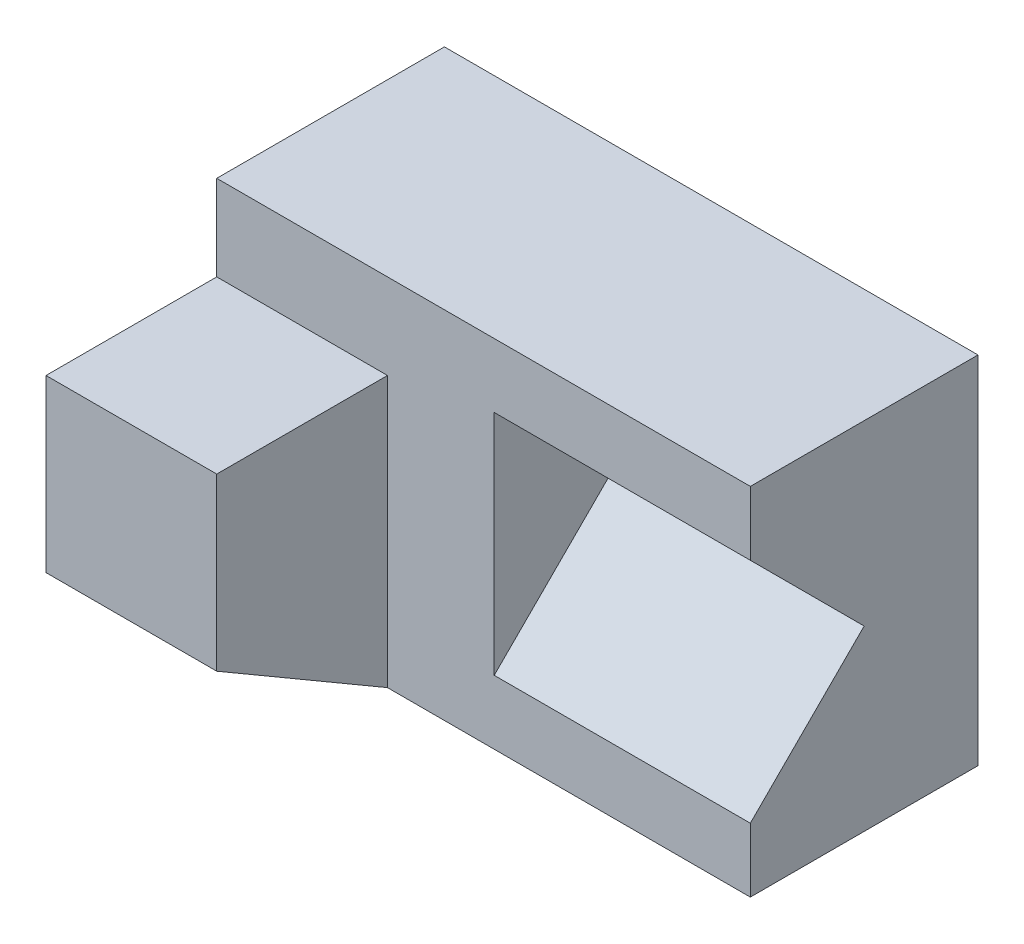
SolidWorks part; units mm, degrees
ref_plane "Front Plane" through (0, 0, 0) normal (0, 0, 1) x (1, 0, 0)
ref_plane "Top Plane" through (0, 0, 0) normal (0, 1, 0) x (1, 0, 0)
ref_plane "Right Plane" through (0, 0, 0) normal (1, 0, 0) x (0, 0, -1)
sketch "Sketch1" plane through (0, 0, 0) normal (0, 0, 1) x (1, 0, 0)
  line L1 (0, 0) -> (75, 0)
  line L2 (0, 0) -> (0, 50)
  line L3 (0, 50) -> (75, 50)
  line L4 (75, 0) -> (75, 50)
  dimension "D1" = 75
  dimension "D2" = 50
extrude "Boss-Extrude1" add sketch "Sketch1" along normal blind 32
sketch "Sketch2" plane through (75, 0, 0) normal (1, 0, 0) x (0, 0, -1)
  line L0 (-32, 41) -> (-16, 25)
  line L1 (-32, 0) -> (-32, 50) construction
  line L2 (-16, 25) -> (-32, 9)
  line L3 (-32, 50) -> (0, 50) construction
  line L4 (-32, 0) -> (0, 0) construction
  line L5 (0, 0) -> (0, 50) construction
  line L6 (-32, 41) -> (-32, 9)
  dimension "D1" = 9
  dimension "D2" = 9
  dimension "D3" = 16
  dimension "D5" = 25
extrude "Cut-Extrude4" cut sketch "Sketch2" against normal blind 36
sketch "Sketch3" plane through (0, 0, 32) normal (0, 0, 1) x (1, 0, 0)
  line L1 (0, 0) -> (24, 0)
  line L2 (0, 0) -> (0, 38)
sketch "Sketch7" plane through (0, 0, 0) normal (-1, 0, 0) x (0, 0, 1)
  line L0 (32, 0) -> (56, 14)
  line L1 (56, 14) -> (56, 38)
  line L2 (56, 38) -> (32, 38)
  line L3 (32, 0) -> (32, 38) construction
  line L4 (32, 38) -> (32, 0)
  dimension "D1" = 24
  dimension "D2" = 24
  dimension "D3" = 38
extrude "Boss-Extrude3" add sketch "Sketch7" against normal blind 24
